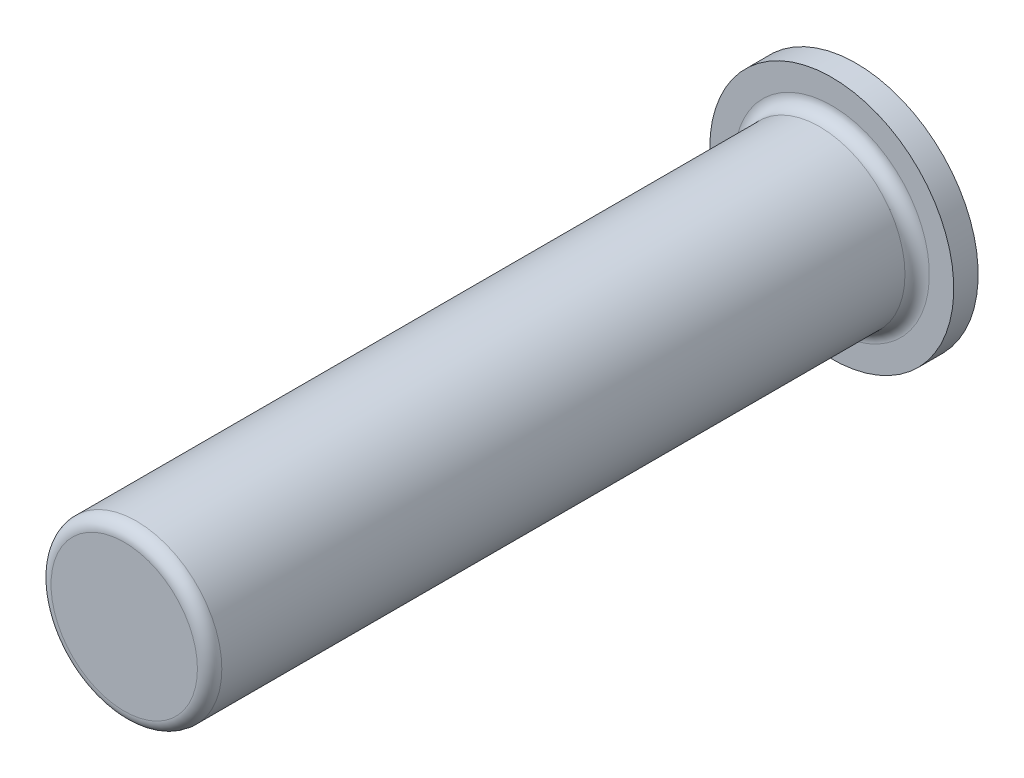
SolidWorks part; units mm, degrees
ref_plane "Front Plane" through (0, 0, 0) normal (0, 0, 1) x (1, 0, 0)
ref_plane "Top Plane" through (0, 0, 0) normal (0, 1, 0) x (1, 0, 0)
ref_plane "Right Plane" through (0, 0, 0) normal (1, 0, 0) x (0, 0, -1)
sketch "Sketch1" plane through (0, 0, 0) normal (0, 0, 1) x (1, 0, 0)
  circle A0 centre (0, 0) radius 14
  circle A1 centre (0, 0) radius 7.5
  dimension "D1" = 28
  dimension "D2" = 15
extrude "Boss-Extrude1" add sketch "Sketch1" along normal blind 120
sketch "Sketch2" plane through (0, 0, 120) normal (0, 0, 1) x (1, 0, 0)
  circle A1 centre (0, 0) radius 14
  circle A2 centre (0, 0) radius 14
  dimension "D1" = 0
extrude "Boss-Extrude2" add sketch "Sketch2" against normal blind 10
sketch "Sketch3" plane through (0, 0, 0) normal (0, 0, -1) x (-1, 0, 0)
  circle A1 centre (0, 0) radius 20
  circle A2 centre (0, 0) radius 7.5 construction
  circle A3 centre (0, 0) radius 7.5
  dimension "D1" = 40
extrude "Boss-Extrude3" add sketch "Sketch3" against normal blind 4
fillet "Fillet3" radius 2 2 edges at (-14, 0, 4) (14, 0, 120)
